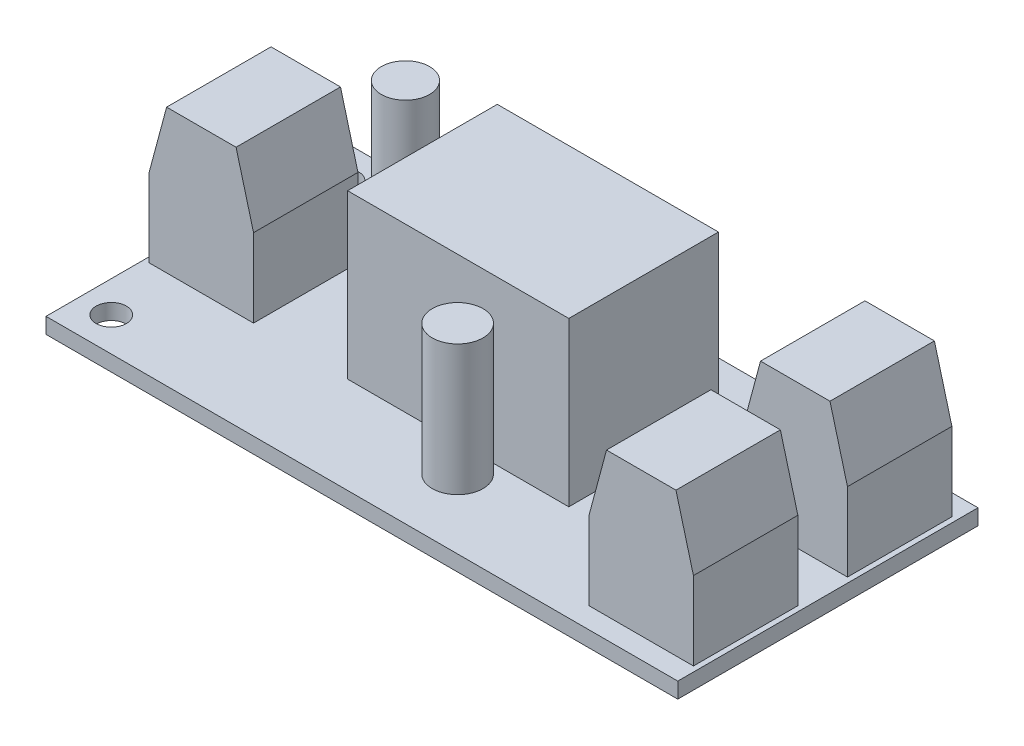
SolidWorks part; units mm, degrees
ref_plane "Front Plane" through (0, 0, 0) normal (0, 0, 1) x (1, 0, 0)
ref_plane "Top Plane" through (0, 0, 0) normal (0, 1, 0) x (1, 0, 0)
ref_plane "Right Plane" through (0, 0, 0) normal (1, 0, 0) x (0, 0, -1)
sketch "Sketch1" plane through (0, 0, 0) normal (0, 1, 0) x (1, 0, 0)
  line L0 (0, 14.605) -> (0, 0) construction
  line L1 (-30.734, 14.605) -> (30.734, 14.605)
  line L2 (-30.734, 14.605) -> (-30.734, -14.605)
  line L3 (-30.734, -14.605) -> (30.734, -14.605)
  line L4 (30.734, 14.605) -> (30.734, -14.605)
  line L5 (0, 0) -> (-30.734, 0) construction
  dimension "D1" = 61.468
  dimension "D2" = 29.21
extrude "Boss-Extrude1" add sketch "Sketch1" along normal mid plane 1.524
hole_wizard "#32 (0.116) Diameter Hole1" positions "Sketch2" profile "Sketch3" hole size "#32" standard "ANSI Inch" end condition up to next
sketch "Sketch2" plane through (0, 0.762, 0) normal (0, 1, 0) x (1, 0, 0)
  line L0 (-27.686, 11.303) -> (-27.686, -11.303) construction
  line L5 (-27.686, 0) -> (0, 0) construction
  line L6 (-30.734, 14.605) -> (-30.734, -14.605) construction
  point P0 (-27.686, 11.303)
  point P2 (-27.686, -11.303)
  dimension "D1" = 22.606
  dimension "D2" = 3.048
sketch "Sketch3" plane through (-27.686, 0.762, -11.303) normal (1, 0, 0) x (0, 0, 1)
  line L0 (0, 0) -> (0, 1.524)
  line L1 (0, 1.524) -> (1.4732, 1.524)
  line L2 (1.4732, 1.524) -> (1.4732, 0)
  line L5 (1.4732, 0) -> (0, 0)
  line L11 (0, -6.35) -> (0, 107.95) construction
  dimension "Thru Hole Dia." = 2.9464
  dimension "Thru Hole Depth" = 1.524
sketch "Sketch4" plane through (0, 0.762, 0) normal (0, 1, 0) x (1, 0, 0)
  line L0 (-30.226, 0) -> (-30.734, 0) construction
  line L1 (-30.226, 5.08) -> (-20.066, 5.08)
  line L2 (-30.226, 5.08) -> (-30.226, -5.08)
  line L3 (-30.226, -5.08) -> (-20.066, -5.08)
  line L4 (-20.066, 5.08) -> (-20.066, -5.08)
  line L5 (-30.734, 14.605) -> (-30.734, -14.605) construction
  dimension "D1" = 10.16
  dimension "D2" = 10.16
  dimension "D3" = 0.508
extrude "Boss-Extrude2" add sketch "Sketch4" along normal blind 13.97
sketch "Sketch5" plane through (0, 0.762, 0) normal (0, 1, 0) x (1, 0, 0)
  line L0 (30.734, -14.605) -> (30.734, 14.605) construction
  line L1 (20.066, 12.573) -> (30.226, 12.573)
  line L2 (20.066, 12.573) -> (20.066, 2.413)
  line L3 (20.066, 2.413) -> (30.226, 2.413)
  line L4 (30.226, 12.573) -> (30.226, 2.413)
  line L5 (20.066, -2.413) -> (30.226, -2.413)
  line L6 (20.066, -2.413) -> (20.066, -12.573)
  line L7 (20.066, -12.573) -> (30.226, -12.573)
  line L8 (30.226, -2.413) -> (30.226, -12.573)
  line L9 (30.734, 14.605) -> (-30.734, 14.605) construction
  line L10 (-30.734, -14.605) -> (30.734, -14.605) construction
  dimension "D1" = 10.16
  dimension "D2" = 10.16
  dimension "D3" = 0.508
  dimension "D4" = 2.032
  dimension "D5" = 2.032
extrude "Boss-Extrude3" add sketch "Sketch5" along normal blind 13.97
chamfer "Chamfer1" distance 6.35 angle 15 6 edges at (-20.066, 14.732, 0) (-30.226, 14.732, 0) (20.066, 14.732, 7.493) (20.066, 14.732, -7.493) (30.226, 14.732, -7.493) (30.226, 14.732, 7.493)
sketch "Sketch6" plane through (0, 0.762, 0) normal (0, 1, 0) x (1, 0, 0)
  circle A0 centre (-20.4202, 10.0514) radius 2.3495
  dimension "D1" = 4.699
extrude "Boss-Extrude4" add sketch "Sketch6" along normal blind 12.7
sketch "Sketch7" plane through (0, 0.762, 0) normal (0, 1, 0) x (1, 0, 0)
  line L1 (-10.7687, 9.3378) -> (10.7493, 9.3378)
  line L2 (-10.7687, 9.3378) -> (-10.7687, -5.2233)
  line L3 (-10.7687, -5.2233) -> (10.7493, -5.2233)
  line L4 (10.7493, 9.3378) -> (10.7493, -5.2233)
extrude "Boss-Extrude5" add sketch "Sketch7" along normal blind 15.875
sketch "Sketch8" plane through (0, 0.762, 0) normal (0, 1, 0) x (1, 0, 0)
  circle A0 centre (2.5746, -7.8648) radius 2.4688
extrude "Boss-Extrude6" add sketch "Sketch8" along normal blind 12.7
